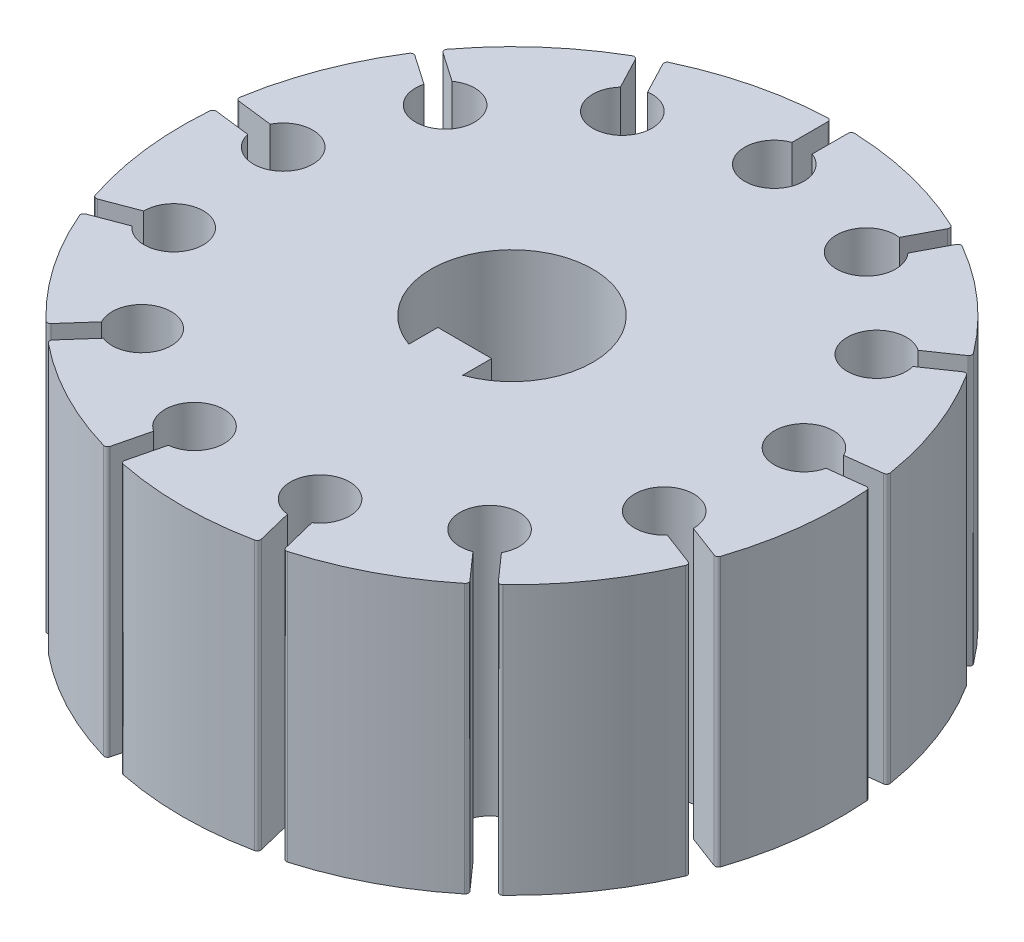
SolidWorks part; units mm, degrees
ref_plane "Front Plane" through (0, 0, 0) normal (0, 0, 1) x (1, 0, 0)
ref_plane "Top Plane" through (0, 0, 0) normal (0, 1, 0) x (1, 0, 0)
ref_plane "Right Plane" through (0, 0, 0) normal (1, 0, 0) x (0, 0, -1)
sketch "Sketch1" plane through (0, 0, 0) normal (0, 1, 0) x (1, 0, 0)
  line L0 (0, -6.01) -> (0, 0) construction
  line L12 (2, -5.6675) -> (2, -3.51)
  line L13 (2, -3.51) -> (-2, -3.51)
  line L14 (-2, -5.6675) -> (-2, -3.51)
  line L15 (2, -5.6675) -> (-2, -5.6675) construction
  circle A0 centre (0, 0) radius 24.5
  arc A6 (2, -5.6675) -> (-2, -5.6675) centre (0, 0) ccw
  arc A8 (-2, -5.6675) -> (2, -5.6675) centre (0, 0) ccw construction
  point P4 (0, -6.01)
  point P6 (0, -6.01)
  point P7 (0, 24.5)
  dimension "D1" = 49
  dimension "D2" = 12.02
  dimension "D3" = 4
  dimension "D4" = 2.5
extrude "Boss-Extrude1" add sketch "Sketch1" along normal blind 20
sketch "Sketch3" plane through (0, 20, 0) normal (0, 1, 0) x (1, 0, 0)
  line L53 (0, 19.5) -> (0, 24.5) construction
  line L54 (0.75, 21.5682) -> (0.75, 24.5)
  line L55 (-0.75, 21.5682) -> (-0.75, 24.5)
  line L56 (0.75, 24.5) -> (-0.75, 24.5)
  arc A2 (-0.75, 21.5682) -> (0.75, 21.5682) centre (0, 19.5) ccw
  circle A3 centre (0, 0) radius 24.5 construction
  point P10 (0, 24.5)
  dimension "D1" = 4.4
  dimension "D2" = 5
  dimension "D3" = 1.5
extrude "Cut-Extrude1" cut sketch "Sketch3" against normal through all
fillet "Fillet1" radius 0.25 2 edges at (-0.75, 10, -24.4885) (0.75, 10, -24.4885)
pattern_circular "CirPattern1" count 13 over 360 about axis through (0, 0, 0) along (0, 1, 0) of "Cut-Extrude1", "Fillet1"
equation "\"shaft_diameter\"= 12.02"
equation "\"outerdiameter\"=49"
equation "\"numberofbars\"= 13"
equation "\"t\"= 20"
equation "\"width\"=1.5"
equation "\"bardiameter\"= 4.4"
equation "\"D1@Sketch1\"=\"outerdiameter\""
equation "\"centerdepth\"= 5"
equation "\"D1@Boss-Extrude1\"= \"t\""
equation "\"key_width\"= 4"
equation "\"key_height\"= 2.5"
equation "\"D1@Sketch3\"=\"bardiameter\""
equation "\"D2@Sketch3\"=\"centerdepth\""
equation "\"D3@Sketch3\"=\"width\""
equation "\"D1@CirPattern1\"=\"numberofbars\""
equation "\"RF1\"= 0.25"
equation "\"D1@Fillet1\"=\"RF1\""
equation "\"D2@Sketch1\"=\"shaft_diameter\""
equation "\"D3@Sketch1\"=\"key_width\""
equation "\"D4@Sketch1\"=\"key_height\""
